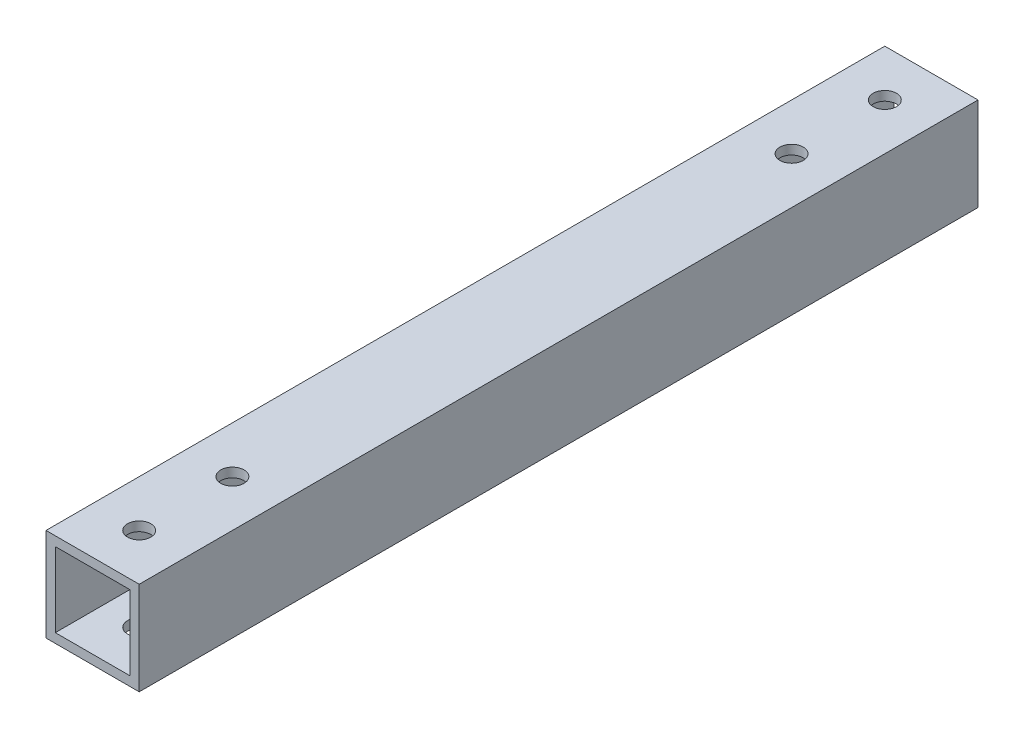
SolidWorks part; units mm, degrees
material "1345 Alloy"
ref_plane "Front Plane" through (0, 0, 0) normal (0, 0, 1) x (1, 0, 0)
ref_plane "Top Plane" through (0, 0, 0) normal (0, 1, 0) x (1, 0, 0)
ref_plane "Right Plane" through (0, 0, 0) normal (1, 0, 0) x (0, 0, -1)
sketch "Sketch1" plane through (0, 0, 0) normal (0, 0, 1) x (1, 0, 0)
  line L1 (-10, 10) -> (10, 10)
  line L2 (-10, 10) -> (-10, -10)
  line L3 (-10, -10) -> (10, -10)
  line L4 (10, 10) -> (10, -10)
  line L5 (-10, 10) -> (10, -10) construction
  line L6 (-10, -10) -> (10, 10) construction
  line L7 (-8, 8) -> (8, 8)
  line L8 (-8, 8) -> (-8, -8)
  line L9 (-8, -8) -> (8, -8)
  line L10 (8, 8) -> (8, -8)
  line L11 (-8, 8) -> (8, -8) construction
  line L12 (-8, -8) -> (8, 8) construction
  point P0 (0, 0)
  point P6 (0, 0)
  dimension "D1" = 20
  dimension "D2" = 20
  dimension "D3" = 16
extrude "Boss-Extrude1" add sketch "Sketch1" along normal blind 180
sketch "Sketch2" plane through (0, 10, 0) normal (0, 1, 0) x (1, 0, 0)
  line L0 (0, 6.4671) -> (0, -187.4374) construction
  line L1 (10, 0) -> (-10, 0) construction
  line L2 (-10, -90) -> (10, -90) construction
  line L3 (-10, -180) -> (-10, 0) construction
  line L4 (10, -180) -> (10, 0) construction
  circle A0 centre (0, -10) radius 2.5
  circle A1 centre (0, -30) radius 2.5
  circle A2 centre (0, -150) radius 2.5
  circle A3 centre (0, -170) radius 2.5
  dimension "D1" = 5
  dimension "D2" = 5
  dimension "D3" = 20
  dimension "D4" = 10
extrude "Cut-Extrude1" cut sketch "Sketch2" against normal through all
